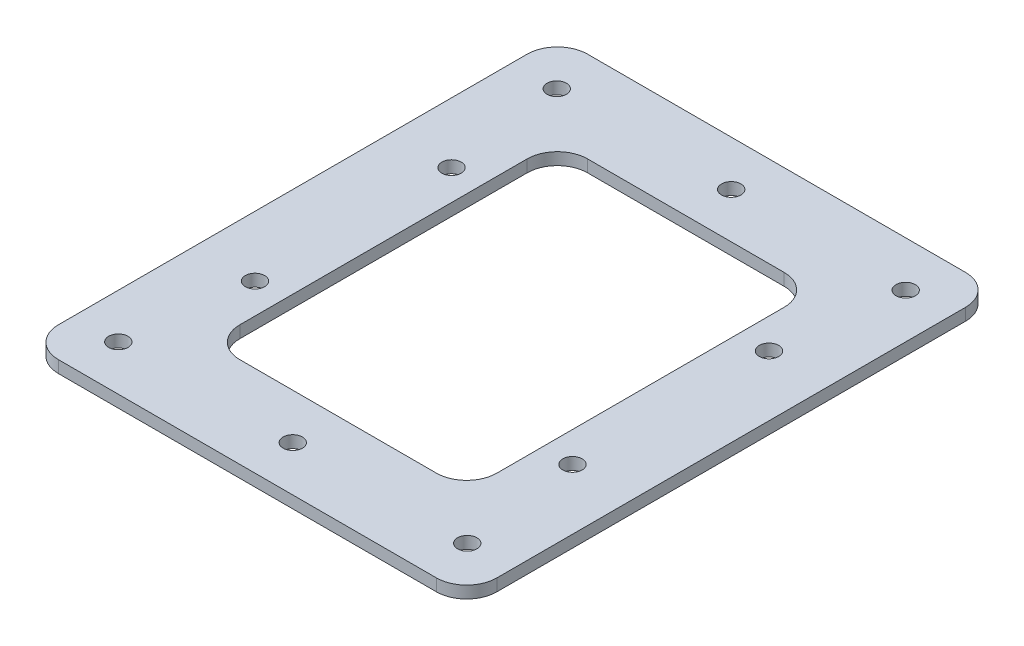
SolidWorks part; units mm, degrees
material "Carbon Fiber"
ref_plane "前视基准面" through (0, 0, 0) normal (0, 0, 1) x (1, 0, 0)
ref_plane "上视基准面" through (0, 0, 0) normal (0, 1, 0) x (1, 0, 0)
ref_plane "右视基准面" through (0, 0, 0) normal (1, 0, 0) x (0, 0, -1)
sketch "草图1" plane through (0, 0, 0) normal (0, 1, 0) x (1, 0, 0)
  line L0 (-15, -15) -> (-15, 72.5)
  line L1 (0, 0) -> (42.5, 0)
  line L2 (0, 0) -> (0, 57.5)
  line L3 (0, 57.5) -> (42.5, 57.5)
  line L4 (42.5, 0) -> (42.5, 57.5)
  line L5 (-15, 72.5) -> (57.5, 72.5)
  line L6 (57.5, -15) -> (57.5, 72.5)
  line L7 (-15, -15) -> (57.5, -15)
  line L8 (-15, 65) -> (-7.6, 65) construction
  line L9 (-7.6, 65) -> (21.25, 65) construction
  line L10 (21.25, 65) -> (50.1, 65) construction
  line L11 (50.1, 65) -> (57.5, 65) construction
  line L12 (-15, -7.5) -> (-7.6, -7.5) construction
  line L13 (-7.6, -7.5) -> (21.25, -7.5) construction
  line L14 (21.25, -7.5) -> (50.1, -7.5) construction
  line L15 (50.1, -7.5) -> (57.5, -7.5) construction
  line L16 (21.25, 65) -> (21.25, 72.5) construction
  line L17 (21.25, -7.5) -> (21.25, -15) construction
  line L18 (0, 28.75) -> (-5, 28.75) construction
  line L19 (-5, 45) -> (-5, 12.5) construction
  circle A0 centre (-7.6, 65) radius 1.6
  circle A1 centre (21.25, 65) radius 1.6
  circle A2 centre (50.1, 65) radius 1.6
  circle A3 centre (50.1, -7.5) radius 1.6
  circle A4 centre (21.25, -7.5) radius 1.6
  circle A5 centre (-7.6, -7.5) radius 1.6
  circle A6 centre (-5, 45) radius 1.6
  circle A7 centre (-5, 12.5) radius 1.6
  circle A8 centre (47.5, 12.5) radius 1.6
  circle A9 centre (47.5, 45) radius 1.6
  dimension "D5" = 3.2
  dimension "D1" = 42.5
  dimension "D2" = 57.5
  dimension "D4" = 7.4
  dimension "D6" = 7.5
  dimension "D7" = 5
  dimension "D8" = 32.5
  dimension "D3" = 15
extrude "凸台-拉伸1" add sketch "草图1" along normal blind 2
fillet "圆角1" radius 5 8 edges at (42.5, 1, -57.5) (42.5, 1, 0) (0, 1, 0) (0, 1, -57.5) (-15, 1, 15) (57.5, 1, 15) (57.5, 1, -72.5) (-15, 1, -72.5)
